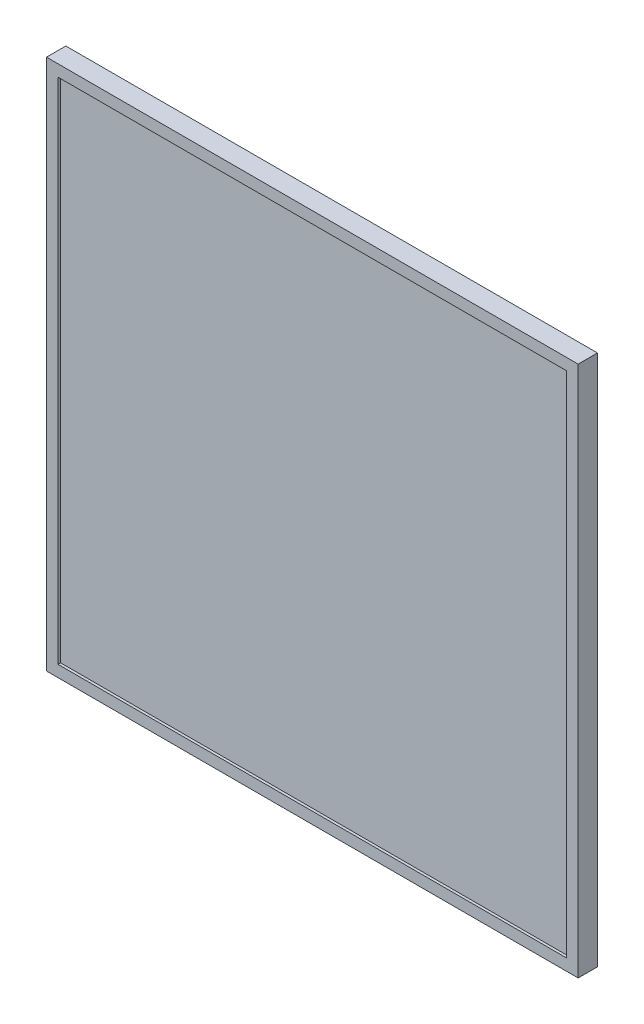
SolidWorks part; units mm, degrees
ref_plane "Ebene vorne" through (0, 0, 0) normal (0, 0, 1) x (1, 0, 0)
ref_plane "Ebene oben" through (0, 0, 0) normal (0, 1, 0) x (1, 0, 0)
ref_plane "Ebene rechts" through (0, 0, 0) normal (1, 0, 0) x (0, 0, -1)
sketch "Skizze1" plane through (0, 0, 0) normal (0, 0, 1) x (1, 0, 0)
  line L5 (0, 0) -> (412.5, 0)
  line L6 (0, 0) -> (0, -412.5)
  line L7 (0, -412.5) -> (412.5, -412.5)
  line L8 (412.5, 0) -> (412.5, -412.5)
  dimension "D1" = 412.5
  dimension "D2" = 412.5
  dimension "D3" = 583.3631
  dimension "D4" = 583.3631
extrude "Aufsatz-Linear austragen1" add sketch "Skizze1" along normal blind 15
sketch "Skizze2" plane through (0, 0, 15) normal (0, 0, 1) x (1, 0, 0)
  line L1 (8.97, -8.97) -> (403.53, -8.97)
  line L2 (8.97, -8.97) -> (8.97, -403.53)
  line L3 (8.97, -403.53) -> (403.53, -403.53)
  line L4 (403.53, -8.97) -> (403.53, -403.53)
  line L5 (0, 0) -> (0, -412.5) construction
  line L6 (412.5, -412.5) -> (412.5, 0) construction
  line L7 (412.5, 0) -> (0, 0) construction
  line L8 (0, -412.5) -> (412.5, -412.5) construction
  dimension "D1" = 394.56
  dimension "D2" = 394.56
  dimension "D3" = 8.97
  dimension "D4" = 8.97
  dimension "D5" = 8.97
  dimension "D6" = 8.97
extrude "Schnitt-Linear austragen1" cut sketch "Skizze2" against normal blind 2
sketch "Skizze3" plane through (412.5, 0, 0) normal (1, 0, 0) x (0, 0, -1)
  line L0 (0, -206.25) -> (146.2917, -360.7357)
  line L1 (125.7391, -368.1191) -> (146.2917, -360.7357)
  line L2 (0, -412.5) -> (0, 0) construction
  line L4 (125.7391, -368.1191) -> (0, -235.3372)
  line L5 (0, -235.3372) -> (0, -206.25)
  line L6 (0.2493, -413.2001) -> (125.7604, -368.1114) construction
  dimension "D1" = 20
  dimension "D3" = 182.8698
  dimension "D4" = 29.0872
extrude "Aufsatz-Linear austragen2" add sketch "Skizze3" along normal blind 100 from offset 256.25
